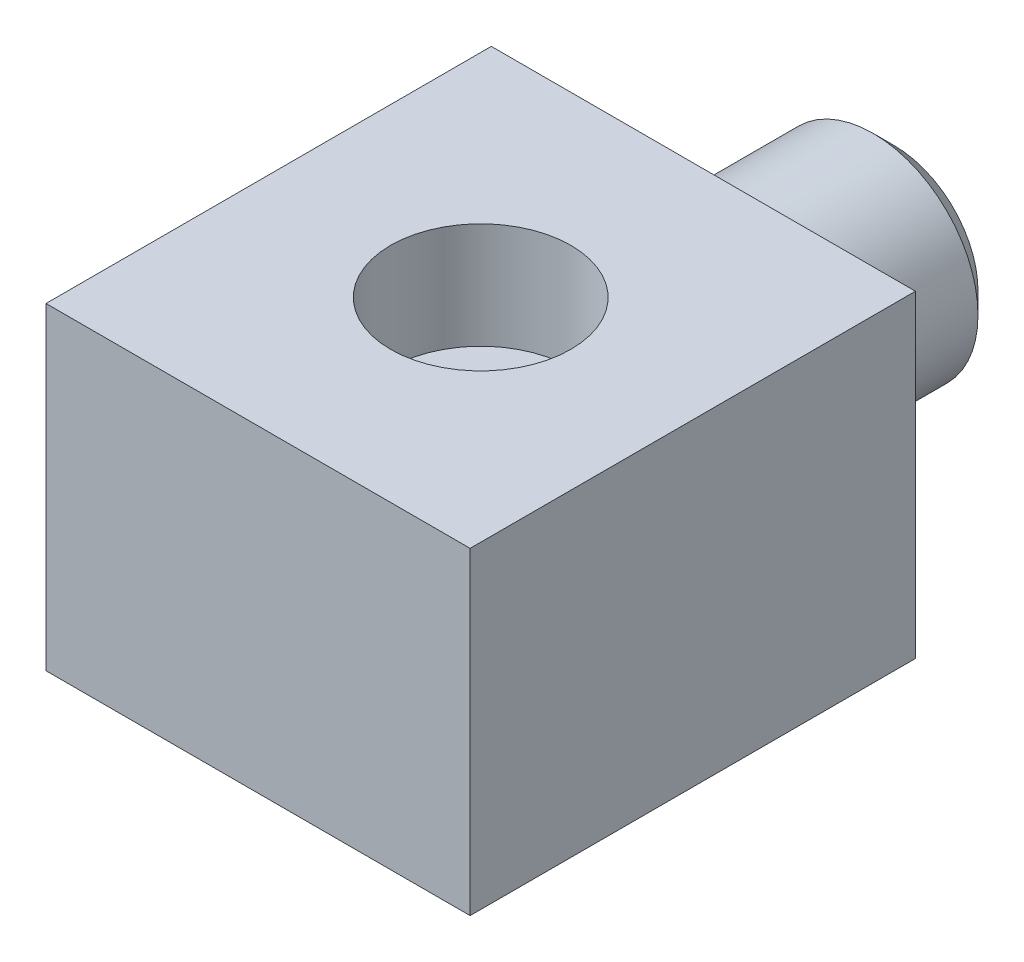
SolidWorks part; units mm, degrees
ref_plane "Front Plane" through (0, 0, 0) normal (0, 0, 1) x (1, 0, 0)
ref_plane "Top Plane" through (0, 0, 0) normal (0, 1, 0) x (1, 0, 0)
ref_plane "Right Plane" through (0, 0, 0) normal (1, 0, 0) x (0, 0, -1)
sketch "Sketch1" plane through (0, 0, 0) normal (1, 0, 0) x (0, 0, -1)
  line L1 (-26.6663, -2.13) -> (-47.6663, -2.13)
  line L2 (-26.6663, -2.13) -> (-26.6663, -17.13)
  line L3 (-26.6663, -17.13) -> (-47.6663, -17.13)
  line L4 (-47.6663, -2.13) -> (-47.6663, -17.13)
  dimension "D1" = 21
  dimension "D2" = 15
extrude "Boss-Extrude1" add sketch "Sketch1" along normal blind 20
sketch "Sketch2" plane through (0, 0, 26.6663) normal (0, 0, -1) x (-1, 0, 0)
  circle A0 centre (-10, -9.63) radius 4.95
  dimension "D1" = 9.9
extrude "Boss-Extrude2" add sketch "Sketch2" along normal blind 9
chamfer "Chamfer1" distance 1 angle 45 1 edges at (10, -4.68, 17.6663)
sketch "Sketch3" plane through (0, -2.13, 0) normal (0, 1, 0) x (1, 0, 0)
  circle A0 centre (10, -37.1663) radius 2.2
  dimension "D1" = 4.4
extrude "Cut-Extrude1" cut sketch "Sketch3" against normal through all contours A0
sketch "Sketch4" plane through (0, -2.13, 0) normal (0, 1, 0) x (1, 0, 0)
  circle A0 centre (10, -37.1663) radius 4.25
  dimension "D1" = 8.5
extrude "Cut-Extrude2" cut sketch "Sketch4" against normal blind 5
